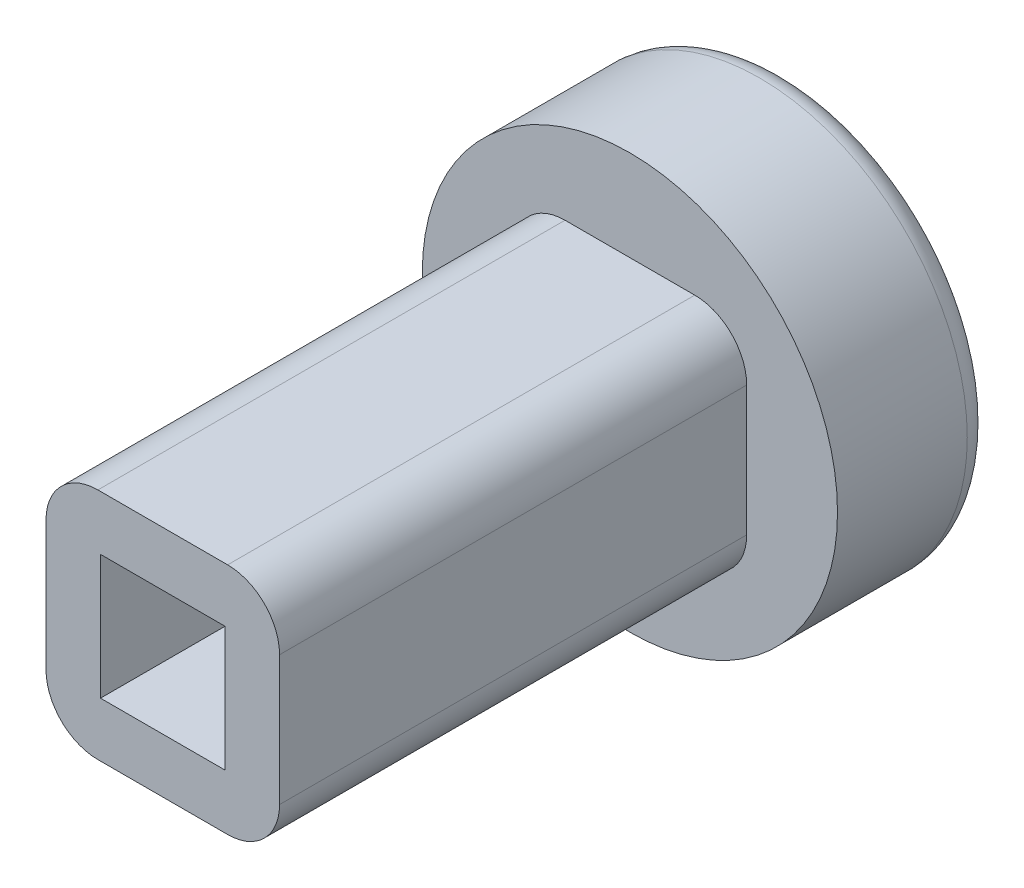
SolidWorks part; units mm, degrees
ref_plane "Plan de face" through (0, 0, 0) normal (0, 0, 1) x (1, 0, 0)
ref_plane "Plan de dessus" through (0, 0, 0) normal (0, 1, 0) x (1, 0, 0)
ref_plane "Plan de droite" through (0, 0, 0) normal (1, 0, 0) x (0, 0, -1)
sketch "Esquisse1" plane through (0, 0, 0) normal (0, 0, 1) x (1, 0, 0)
  circle A0 centre (0, 0) radius 4
  dimension "D1" = 8
extrude "Boss.-Extru.1" add sketch "Esquisse1" along normal blind 3
sketch "Esquisse2" plane through (0, 0, 3) normal (0, 0, 1) x (1, 0, 0)
  line L1 (2.25, 2.25) -> (-2.25, 2.25)
  line L2 (2.25, 2.25) -> (2.25, -2.25)
  line L3 (2.25, -2.25) -> (-2.25, -2.25)
  line L4 (-2.25, 2.25) -> (-2.25, -2.25)
  line L5 (2.25, 2.25) -> (-2.25, -2.25) construction
  line L6 (2.25, -2.25) -> (-2.25, 2.25) construction
  line L11 (-1.2559, -1.2559) -> (1.2559, 1.2559) construction
  line L12 (-1.2559, 1.2559) -> (1.2559, -1.2559) construction
  point P0 (0, 0)
  point P6 (0, 0)
  point P11 (0, 0)
  point P12 (1.2781, 1.2781)
  point P13 (1.2432, 1.2432)
  point P14 (1.2559, 1.2559)
  dimension "D1" = 4.5
  dimension "D2" = 4.5
  dimension "D3" = 2.5118
extrude "Boss.-Extru.2" add sketch "Esquisse2" along normal blind 9
sketch "Esquisse3" plane through (0, 0, 12) normal (0, 0, 1) x (1, 0, 0)
  line L1 (1.2, 1.2) -> (-1.2, 1.2)
  line L2 (1.2, 1.2) -> (1.2, -1.2)
  line L3 (1.2, -1.2) -> (-1.2, -1.2)
  line L4 (-1.2, 1.2) -> (-1.2, -1.2)
  line L5 (1.2, 1.2) -> (-1.2, -1.2) construction
  line L6 (1.2, -1.2) -> (-1.2, 1.2) construction
  point P0 (0, 0)
  dimension "D1" = 2.4
extrude "Enlèv. mat.-Extru.1" cut sketch "Esquisse3" against normal blind 3
fillet "Congé1" radius 1 4 edges at (-2.25, 2.25, 7.5) (2.25, 2.25, 7.5) (2.25, -2.25, 7.5) (-2.25, -2.25, 7.5)
fillet "Congé2" radius 0.5 1 edges at (4, 0, 0)
